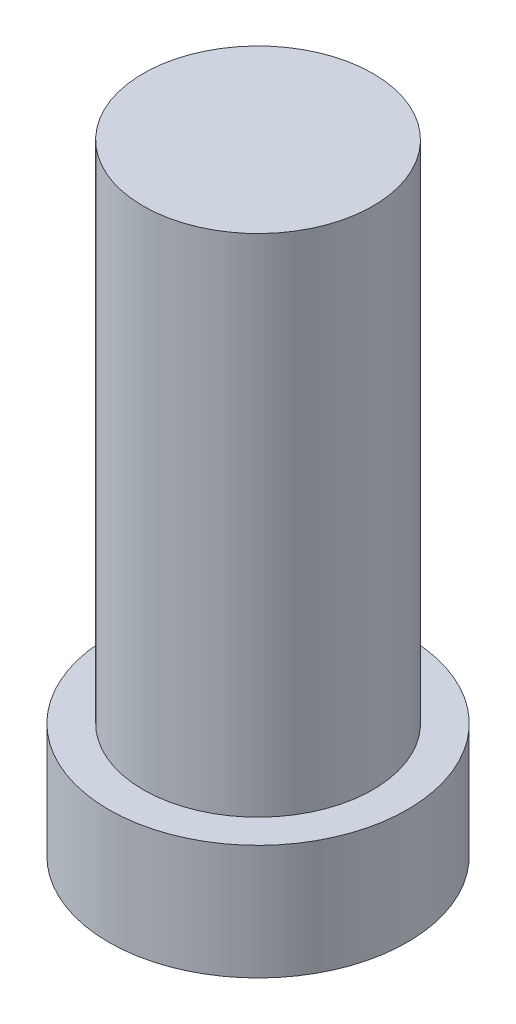
SolidWorks part; units mm, degrees
ref_plane "前视基准面" through (0, 0, 0) normal (0, 0, 1) x (1, 0, 0)
ref_plane "上视基准面" through (0, 0, 0) normal (0, 1, 0) x (1, 0, 0)
ref_plane "右视基准面" through (0, 0, 0) normal (1, 0, 0) x (0, 0, -1)
other "Configuration Table"
sketch "草图1" plane through (0, 0, 0) normal (0, 1, 0) x (1, 0, 0)
  circle A0 centre (0, 0) radius 6.5
  dimension "D1" = 13
extrude "凸台-拉伸1" add sketch "草图1" along normal blind 5
ref_plane "基准面1" through (0, 5, 0) normal (0, 1, 0) x (1, 0, 0)
sketch "草图2" plane through (0, 5, 0) normal (0, 1, 0) x (1, 0, 0)
  circle A0 centre (0, 0) radius 5
  dimension "D1" = 10
extrude "凸台-拉伸2" add sketch "草图2" along normal blind 22
cosmetic thread "装饰螺纹线1"
ref_plane "基准面2" through (0, 0, 0) normal (0, -1, 0) x (-1, 0, 0)
sketch "草图3" plane through (0, 0, 0) normal (0, -1, 0) x (-1, 0, 0)
  line L0 (0, 0) -> (5.9062, 0) construction
  line L1 (0, 0) -> (0, 5.01) construction
  line L3 (-1.7667, 5.1003) -> (1.7667, 5.1003)
  line L4 (-1.7667, 5.1003) -> (-1.7667, -5.1003)
  line L5 (-1.7667, -5.1003) -> (1.7667, -5.1003)
  line L6 (1.7667, 5.1003) -> (1.7667, -5.1003)
extrude "切除-拉伸1" cut sketch "草图3" against normal blind 3
